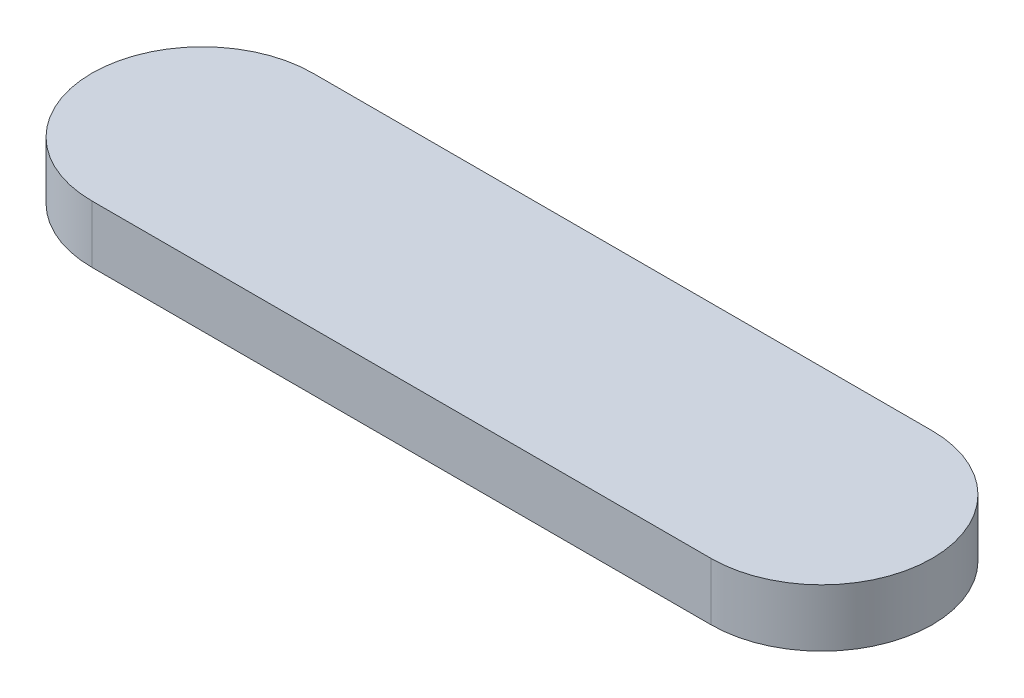
SolidWorks part; units mm, degrees
ref_plane "Front Plane" through (0, 0, 0) normal (0, 0, 1) x (1, 0, 0)
ref_plane "Top Plane" through (0, 0, 0) normal (0, 1, 0) x (1, 0, 0)
ref_plane "Right Plane" through (0, 0, 0) normal (1, 0, 0) x (0, 0, -1)
sketch "Sketch1" plane through (0, 0, 0) normal (0, 1, 0) x (1, 0, 0)
  line L0 (0, 0) -> (-50000, 0) construction
  line L1 (0, 0) -> (0, -50000) construction
  line L2 (0, 25) -> (140, 25)
  line L3 (0, -25) -> (140, -25)
  arc A0 (0, 25) -> (0, -25) centre (0, 0) ccw
  arc A1 (140, -25) -> (140, 25) centre (140, 0) ccw
  dimension "D1" = 140
  dimension "D2" = 25
extrude "Boss-Extrude1" add sketch "Sketch1" along normal blind 13
